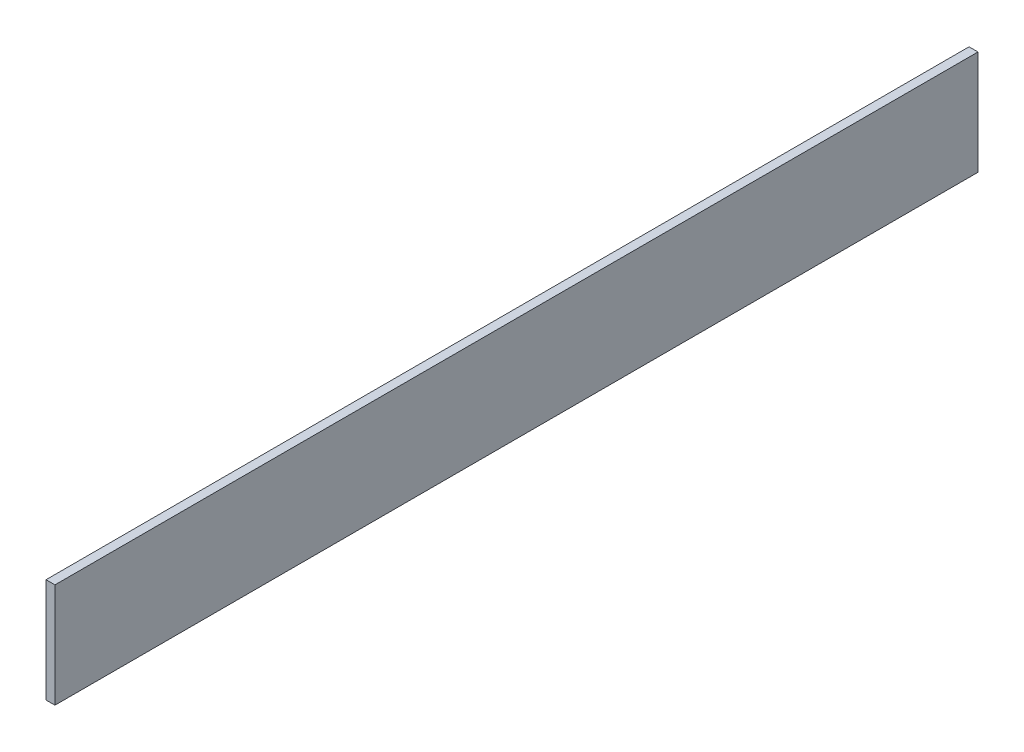
SolidWorks part; units mm, degrees
ref_plane "Ön Düzlem" through (0, 0, 0) normal (0, 0, 1) x (1, 0, 0)
ref_plane "Üst Düzlem" through (0, 0, 0) normal (0, 1, 0) x (1, 0, 0)
ref_plane "Sağ Düzlem" through (0, 0, 0) normal (1, 0, 0) x (0, 0, -1)
sketch "Çizim1" plane through (0, 0, 0) normal (1, 0, 0) x (0, 0, -1)
  line L1 (0, 0) -> (310, 0)
  line L2 (0, 0) -> (0, 35)
  line L3 (0, 35) -> (310, 35)
  line L4 (310, 0) -> (310, 35)
  dimension "D1" = 35
  dimension "D2" = 310
extrude "Yükseklik-Ekstrüzyon1" add sketch "Çizim1" along normal blind 3
